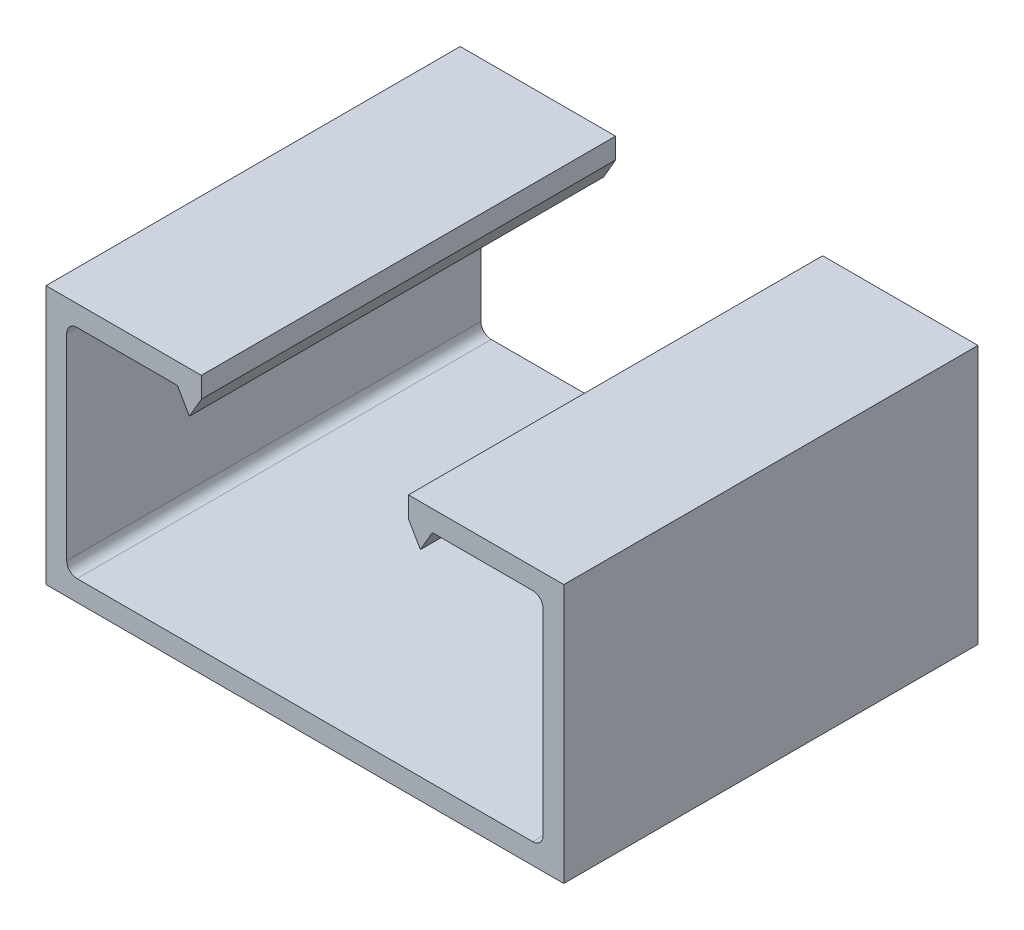
SolidWorks part; units mm, degrees
ref_plane "Plane1" through (0, 0, 0) normal (0, 0, 1) x (1, 0, 0)
ref_plane "Plane2" through (0, 0, 0) normal (0, 1, 0) x (1, 0, 0)
ref_plane "Plane3" through (0, 0, 0) normal (1, 0, 0) x (0, 0, -1)
sketch "Sketch1" plane through (0, 0, 0) normal (0, 0, 1) x (1, 0, 0)
  line L0 (-6.35, 7.9375) -> (-15.875, 7.9375)
  line L1 (-15.875, 7.9375) -> (-15.875, -7.9375)
  line L2 (-15.875, -7.9375) -> (15.875, -7.9375)
  line L3 (15.875, -7.9375) -> (15.875, 7.9375)
  line L4 (15.875, 7.9375) -> (6.35, 7.9375)
  line L5 (13.97, 6.6675) -> (7.8165, 6.6675)
  line L6 (14.605, -6.0325) -> (14.605, 6.0325)
  line L7 (-13.97, -6.6675) -> (13.97, -6.6675)
  line L8 (-14.605, 6.0325) -> (-14.605, -6.0325)
  line L9 (-7.8165, 6.6675) -> (-13.97, 6.6675)
  line L10 (7.8165, 6.6675) -> (7.0832, 5.3975)
  line L11 (7.0832, 5.3975) -> (6.35, 6.6675)
  line L12 (6.35, 6.6675) -> (6.35, 7.9375)
  line L13 (-7.8165, 6.6675) -> (-7.0832, 5.3975)
  line L14 (-7.0832, 5.3975) -> (-6.35, 6.6675)
  line L15 (-6.35, 6.6675) -> (-6.35, 7.9375)
  arc A0 (-14.605, -6.0325) -> (-13.97, -6.6675) centre (-13.97, -6.0325) ccw
  arc A1 (-13.97, 6.6675) -> (-14.605, 6.0325) centre (-13.97, 6.0325) ccw
  arc A2 (14.605, 6.0325) -> (13.97, 6.6675) centre (13.97, 6.0325) ccw
  arc A3 (13.97, -6.6675) -> (14.605, -6.0325) centre (13.97, -6.0325) ccw
  dimension "D5" = 0.635
  dimension "Width" = 31.75
  dimension "Height" = 15.875
  dimension "D8" = 15.875
  dimension "D9" = 7.9375
  dimension "D10" = 12.7
  dimension "edge" = 9.525
  dimension "D13" = 0.7332
  dimension "D4" = 60
extrude "Base-Extrude" add sketch "Sketch1" along normal mid plane 25.4
equation "\"D8@Sketch1\" = \"Width@Sketch1\" / 2"
equation "\"D9@Sketch1\" = \"Height@Sketch1\" / 2"
equation "\"D10@Sketch1\" = \"Width@Sketch1\" - 2 * \"edge@Sketch1\""
equation "\"D5@Sketch1\" = \"gauge@Sketch1\" / 2"
equation "\"D13@Sketch1\" = \"gauge@Sketch1\" * .577350269"
